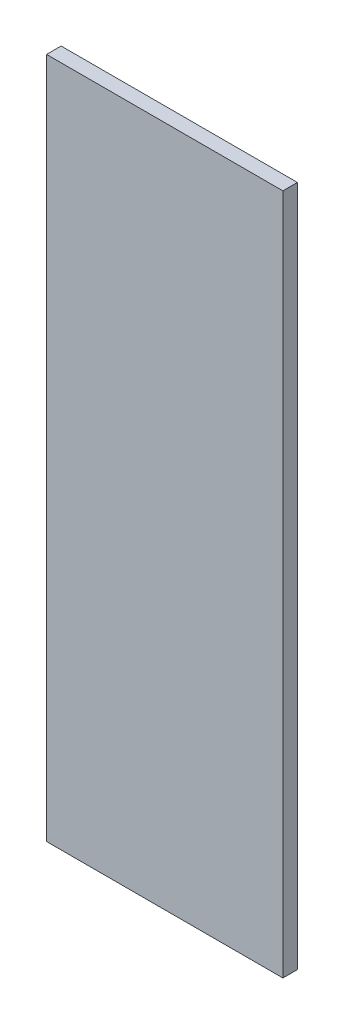
SolidWorks part; units mm, degrees
material "Plastique personnalisé"
ref_plane "Plan de face" through (0, 0, 0) normal (0, 0, 1) x (1, 0, 0)
ref_plane "Plan de dessus" through (0, 0, 0) normal (0, 1, 0) x (1, 0, 0)
ref_plane "Plan de droite" through (0, 0, 0) normal (1, 0, 0) x (0, 0, -1)
sketch "Esquisse1" plane through (0, 0, 0) normal (0, 0, 1) x (1, 0, 0)
  line L1 (-13, -37.5) -> (13, -37.5)
  line L2 (-13, -37.5) -> (-13, 37.5)
  line L3 (-13, 37.5) -> (13, 37.5)
  line L4 (13, -37.5) -> (13, 37.5)
  line L5 (-13, -37.5) -> (13, 37.5) construction
  line L6 (-13, 37.5) -> (13, -37.5) construction
  point P0 (0, 0)
  dimension "D1" = 26
  dimension "D2" = 75
extrude "Boss.-Extru.1" add sketch "Esquisse1" along normal blind 1.6
